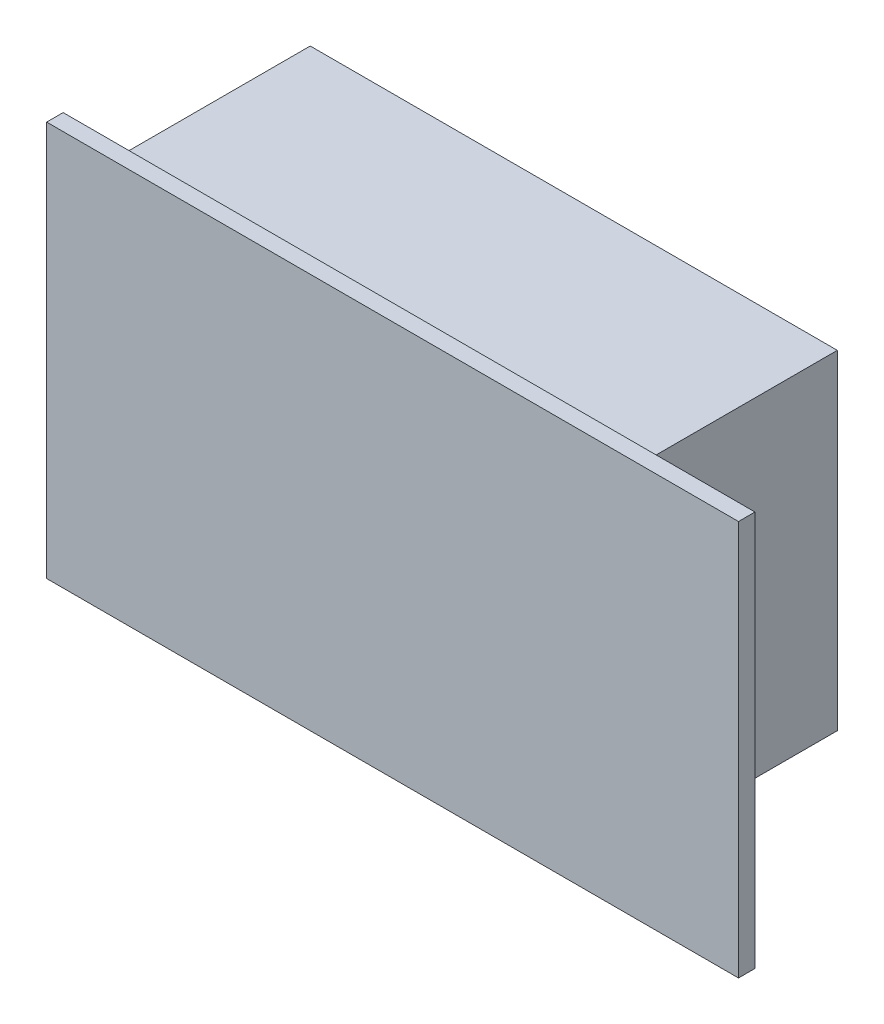
SolidWorks part; units mm, degrees
ref_plane "Plan de face" through (0, 0, 0) normal (0, 0, 1) x (1, 0, 0)
ref_plane "Plan de dessus" through (0, 0, 0) normal (0, 1, 0) x (1, 0, 0)
ref_plane "Plan de droite" through (0, 0, 0) normal (1, 0, 0) x (0, 0, -1)
sketch "Esquisse2" plane through (0, 0, 0) normal (0, 0, 1) x (1, 0, 0)
  line L1 (0, 0) -> (4.2, 0)
  line L2 (0, 0) -> (0, 2.4)
  line L3 (0, 2.4) -> (4.2, 2.4)
  line L4 (4.2, 0) -> (4.2, 2.4)
  dimension "D1" = 4.2
  dimension "D2" = 2.4
extrude "Boss.-Extru.1" add sketch "Esquisse2" along normal blind 0.1
sketch "Esquisse3" plane through (0, 0, 0) normal (0, 0, -1) x (-1, 0, 0)
  line L0 (-1.8, 2.2) -> (-1.8, 2.4) construction
  line L1 (-3.4, 2.2) -> (-0.2, 2.2)
  line L2 (-3.4, 2.2) -> (-3.4, 0.2)
  line L3 (-3.4, 0.2) -> (-0.2, 0.2)
  line L4 (-0.2, 2.2) -> (-0.2, 0.2)
  line L5 (-4.2, 2.4) -> (0, 2.4) construction
  line L6 (-1.8, 0.2) -> (-1.8, 0) construction
  line L7 (0, 0) -> (-4.2, 0) construction
  line L8 (0, 2.4) -> (0, 0) construction
  dimension "D1" = 2
  dimension "D2" = 3.2
  dimension "D3" = 0.2
extrude "Boss.-Extru.2" add sketch "Esquisse3" along normal blind 1.3
sketch "Esquisse4" plane through (0, 0, -1.3) normal (0, 0, -1) x (-1, 0, 0)
  line L0 (-3.3, 2.1) -> (-3.3, 2.2) construction
  line L1 (-3.3, 2.1) -> (-0.3, 2.1)
  line L2 (-3.3, 2.1) -> (-3.3, 0.3)
  line L3 (-3.3, 0.3) -> (-0.3, 0.3)
  line L4 (-0.3, 2.1) -> (-0.3, 0.3)
  line L6 (-0.2, 2.2) -> (-3.4, 2.2) construction
  line L7 (-3.3, 0.3) -> (-3.3, 0.2) construction
  line L8 (-3.4, 0.2) -> (-0.2, 0.2) construction
  line L9 (-3.3, 2.1) -> (-3.4, 2.1) construction
  line L10 (-3.4, 2.2) -> (-3.4, 0.2) construction
  line L11 (-0.3, 2.1) -> (-0.2, 2.1) construction
  line L12 (-0.2, 0.2) -> (-0.2, 2.2) construction
  dimension "D1" = 3
  dimension "D2" = 1.8
extrude "Enlèv. mat.-Extru.1" cut sketch "Esquisse4" against normal blind 0.01
